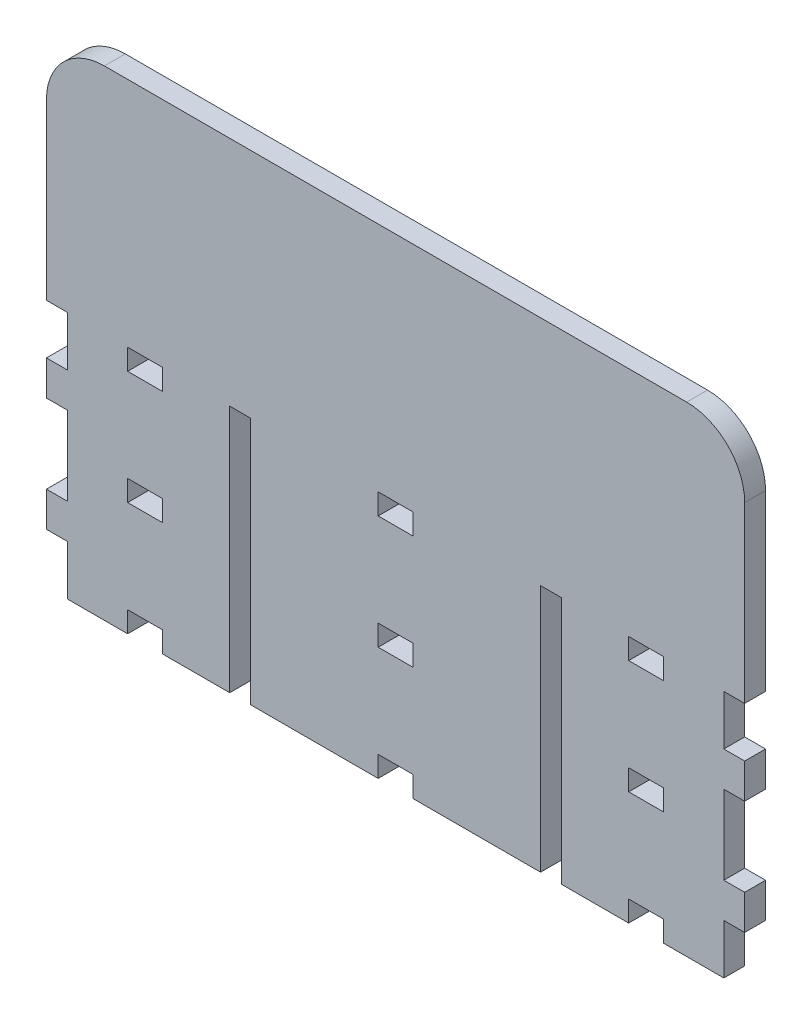
SolidWorks part; units mm, degrees
ref_plane "Plan de face" through (0, 0, 0) normal (0, 0, 1) x (1, 0, 0)
ref_plane "Plan de dessus" through (0, 0, 0) normal (0, 1, 0) x (1, 0, 0)
ref_plane "Plan de droite" through (0, 0, 0) normal (1, 0, 0) x (0, 0, -1)
sketch "Esquisse1" plane through (0, 0, 0) normal (0, 0, 1) x (1, 0, 0)
  line L1 (-584, 400) -> (18, 400)
  line L2 (-584, 400) -> (-584, 764)
  line L3 (-534, 814) -> (-32, 814)
  line L4 (18, 400) -> (18, 764)
  line L8 (18, 614) -> (18, 571) construction
  line L9 (-584, 614) -> (-584, 571) construction
  line L10 (-566, 614) -> (-584, 614) construction
  arc A0 (-584, 764) -> (-534, 814) centre (-534, 764) cw
  arc A1 (-32, 814) -> (18, 764) centre (-32, 764) cw
  dimension "D2" = 50
  dimension "D1" = 200
extrude "Boss.-Extru.1" add sketch "Esquisse1" against normal blind 18
sketch "Esquisse2" plane through (0, 0, 0) normal (0, 0, 1) x (1, 0, 0)
  line L0 (-584, 400) -> (18, 400) construction
  line L1 (-514, 614) -> (-484, 614)
  line L2 (-514, 614) -> (-514, 596)
  line L3 (-514, 596) -> (-484, 596)
  line L4 (-484, 614) -> (-484, 596)
  line L5 (-298, 614) -> (-268, 614)
  line L6 (-298, 614) -> (-298, 596)
  line L7 (-298, 596) -> (-268, 596)
  line L8 (-268, 614) -> (-268, 596)
  line L9 (-82, 614) -> (-52, 614)
  line L10 (-82, 614) -> (-82, 596)
  line L11 (-82, 596) -> (-52, 596)
  line L12 (-52, 614) -> (-52, 596)
  line L13 (-82, 516) -> (-52, 516)
  line L14 (-82, 516) -> (-82, 498)
  line L15 (-82, 498) -> (-52, 498)
  line L16 (-52, 516) -> (-52, 498)
  line L17 (-298, 516) -> (-268, 516)
  line L18 (-298, 516) -> (-298, 498)
  line L19 (-298, 498) -> (-268, 498)
  line L20 (-268, 516) -> (-268, 498)
  line L21 (-514, 516) -> (-484, 516)
  line L22 (-514, 516) -> (-514, 498)
  line L23 (-514, 498) -> (-484, 498)
  line L24 (-484, 516) -> (-484, 498)
  line L25 (-514, 418) -> (-484, 418)
  line L26 (-514, 418) -> (-514, 400)
  line L27 (-514, 400) -> (-484, 400)
  line L28 (-484, 418) -> (-484, 400)
  line L29 (-484, 400) -> (-484, 418) construction
  line L30 (-268, 400) -> (-268, 418) construction
  line L31 (-298, 418) -> (-268, 418)
  line L32 (-298, 418) -> (-298, 400)
  line L33 (-298, 400) -> (-268, 400)
  line L34 (-268, 418) -> (-268, 400)
  line L35 (-514, 605) -> (-584, 605) construction
  line L36 (-82, 418) -> (-52, 418)
  line L37 (-82, 418) -> (-82, 400)
  line L38 (-82, 400) -> (-52, 400)
  line L39 (-52, 418) -> (-52, 400)
  line L40 (-584, 764) -> (-584, 400) construction
  line L41 (-484, 605) -> (-298, 605) construction
  line L42 (-268, 605) -> (-82, 605) construction
  line L43 (-52, 605) -> (18, 605) construction
  line L44 (18, 400) -> (18, 764) construction
extrude "Enlèv. mat.-Extru.1" cut sketch "Esquisse2" against normal through all
sketch "Esquisse3" plane through (0, 0, 0) normal (0, 0, 1) x (1, 0, 0)
  line L0 (0, 614) -> (0, 10) construction
  line L1 (0, 443) -> (18, 443)
  line L2 (0, 443) -> (0, 400)
  line L3 (0, 400) -> (18, 400)
  line L4 (18, 443) -> (18, 400)
  line L5 (18, 400) -> (18, 764) construction
  line L6 (0, 473) -> (18, 473)
  line L7 (0, 473) -> (0, 541)
  line L8 (0, 541) -> (18, 541)
  line L9 (18, 473) -> (18, 541)
  line L10 (0, 541) -> (18, 541) construction
  line L11 (-584, 764) -> (-584, 400) construction
  line L12 (0, 571) -> (18, 571)
  line L13 (0, 571) -> (0, 614)
  line L14 (0, 614) -> (18, 614)
  line L15 (18, 571) -> (18, 614)
  line L16 (-566, 443) -> (-584, 443)
  line L17 (-566, 443) -> (-566, 400)
  line L18 (-566, 400) -> (-584, 400)
  line L19 (-584, 443) -> (-584, 400)
  line L20 (-584, 541) -> (-566, 541) construction
  line L21 (-566, 473) -> (-584, 473)
  line L22 (-566, 473) -> (-566, 541)
  line L23 (-566, 541) -> (-584, 541)
  line L24 (-584, 473) -> (-584, 541)
  line L25 (-566, 571) -> (-584, 571)
  line L26 (-566, 571) -> (-566, 614)
  line L27 (-566, 614) -> (-584, 614)
  line L28 (-584, 571) -> (-584, 614)
  line L29 (-584, 400) -> (-514, 400) construction
  line L30 (18, 614) -> (-584, 614) construction
  line L31 (18, 614) -> (0, 614) construction
  line L32 (0, 443) -> (18, 443) construction
extrude "Enlèv. mat.-Extru.2" cut sketch "Esquisse3" against normal through all
sketch "Esquisse4" plane through (0, 0, 0) normal (0, 0, 1) x (1, 0, 0)
  line L0 (-484, 400) -> (-298, 400) construction
  line L1 (-408, 400) -> (-426, 400)
  line L2 (-408, 400) -> (-408, 614)
  line L3 (-408, 614) -> (-426, 614)
  line L4 (-426, 400) -> (-426, 614)
  line L5 (-408, 614) -> (-408, 253.4124) construction
  line L6 (-268, 400) -> (-82, 400) construction
  line L7 (-158, 400) -> (-140, 400)
  line L8 (-158, 400) -> (-158, 614)
  line L9 (-158, 614) -> (-140, 614)
  line L10 (-140, 400) -> (-140, 614)
  line L11 (-158, 614) -> (-158, 253.4124) construction
extrude "Enlèv. mat.-Extru.3" cut sketch "Esquisse4" against normal blind 18
sketch "Esquisse6" plane through (0, 0, -18) normal (0, 0, 1) x (1, 0, 0)
  line L0 (-490.5423, 716.0008) -> (-490.5423, 701.5979)
  line L1 (-488.7785, 699.5812) -> (-488.7785, 717.8116)
  line L2 (-479.2535, 724.3917) -> (-479.2535, 693.0885)
  line L3 (-477.0486, 691.0866) -> (-477.0486, 726.1757)
  line L4 (-390.7062, 725.3692) -> (-390.7062, 690.4251)
  line L5 (-388.5014, 692.4312) -> (-388.5014, 723.353)
  line L6 (-379.0646, 716.7748) -> (-379.0646, 698.7223)
  line L7 (-377.3007, 700.9795) -> (-377.3007, 715.0627)
  line L8 (-477.0486, 726.1757) -> (-477.0486, 691.0866)
  line L9 (-390.7062, 690.4251) -> (-390.7062, 725.3692)
  line L10 (-488.7785, 717.8116) -> (-488.7785, 699.5812)
  line L11 (-479.2535, 693.0885) -> (-479.2535, 724.3917)
  line L12 (-388.5014, 723.353) -> (-388.5014, 692.4312)
  line L13 (-379.0646, 698.7223) -> (-379.0646, 716.7748)
  line L14 (-490.5423, 701.5979) -> (-490.5423, 716.0008)
  line L15 (-377.3007, 715.0627) -> (-377.3007, 700.9795)
  line L16 (-584, 714) -> (-433.5, 714) construction
  line L19 (-584, 764) -> (-584, 614) construction
  line L20 (-433.5, 714) -> (-283, 714) construction
  line L21 (-132.5, 714) -> (18, 714) construction
  line L22 (18, 614) -> (18, 764) construction
  line L23 (-283, 714) -> (-283, 814) construction
  line L24 (-32, 814) -> (-534, 814) construction
  line L25 (-283, 714) -> (-132.5, 714) construction
  line L26 (-508.2295, 707.4612) -> (-358.7705, 720.5388) construction
  line L27 (-283, 714) -> (-283, 614) construction
  line L28 (-268, 614) -> (-298, 614) construction
  line L29 (-207.242, 707.8567) -> (-57.758, 720.1433) construction
  spline S0 degree 3 poles (-167.9941, 780.5511) (-159.6923, 785.0594) (-149.9682, 788.1975) (-138.6433, 789.0831) knots 8 8 8 8 9 9 9 9
  spline S1 degree 3 poles (-188.8125, 763.828) (-183.1553, 770.3743) (-176.5566, 775.901) (-167.9941, 780.5511) knots 7 7 7 7 8 8 8 8
  spline S2 degree 3 poles (-207.242, 707.8567) (-209.3608, 732.9454) (-200.0954, 750.7719) (-188.8125, 763.828) knots 6 6 6 6 7 7 7 7
  spline S3 degree 3 poles (-182.3283, 658.0286) (-195.8761, 669.7994) (-205.3943, 685.9735) (-207.242, 707.8567) knots 5 5 5 5 6 6 6 6
  spline S4 degree 3 poles (-126.3571, 639.599) (-150.3082, 637.6326) (-169.3815, 646.78) (-182.3283, 658.0286) knots 4 4 4 4 5 5 5 5
  spline S5 degree 3 poles (-76.5286, 664.5129) (-88.3918, 650.9871) (-103.9374, 641.4394) (-126.3571, 639.599) knots 3 3 3 3 4 4 4 4
  spline S6 degree 3 poles (-57.758, 720.1433) (-55.8242, 695.4161) (-64.8483, 677.8317) (-76.5286, 664.5129) knots 2 2 2 2 3 3 3 3
  spline S7 degree 3 poles (-82.3311, 770.3125) (-69.5426, 759.036) (-59.5119, 742.5654) (-57.758, 720.1433) knots 1 1 1 1 2 2 2 2
  spline S8 degree 3 poles (-138.6433, 789.0831) (-114.19, 790.9955) (-95.1366, 781.6038) (-82.3311, 770.3125) knots 0 0 0 0 1 1 1 1
  spline S9 degree 3 poles (-174.1371, 731.4055) (-172.0509, 731.6973) (-172.8434, 734.2081) (-172.7721, 735.1596) knots 16 16 16 16 17 17 17 17
  spline S10 degree 3 poles (-176.185, 739.5964) (-176.082, 736.8451) (-176.745, 732.0371) (-174.1371, 731.4055) knots 15 15 15 15 16 16 16 16
  spline S11 degree 3 poles (-175.844, 751.5414) (-176.5898, 748.4845) (-176.3518, 744.0505) (-176.185, 739.5964) knots 14 14 14 14 15 15 15 15
  spline S12 degree 3 poles (-137.6194, 777.8207) (-154.7803, 776.5585) (-172.0452, 767.1012) (-175.844, 751.5414) knots 13 13 13 13 14 14 14 14
  spline S13 degree 3 poles (-114.4115, 773.7252) (-122.2829, 776.2977) (-128.8265, 778.4676) (-137.6194, 777.8207) knots 12 12 12 12 13 13 13 13
  spline S14 degree 3 poles (-99.7368, 767.5821) (-103.0613, 770.1785) (-108.7891, 771.8874) (-114.4115, 773.7252) knots 11 11 11 11 12 12 12 12
  spline S15 degree 3 poles (-90.8633, 753.5891) (-91.6605, 758.6655) (-96.7933, 765.2835) (-99.7368, 767.5821) knots 10 10 10 10 11 11 11 11
  spline S16 degree 3 poles (-91.8871, 737.549) (-91.0445, 741.3206) (-90.4619, 751.0313) (-90.8633, 753.5891) knots 9 9 9 9 10 10 10 10
  spline S17 degree 3 poles (-94.617, 742.3266) (-94.8434, 740.0665) (-96.3113, 734.5149) (-93.9342, 734.1357) (-92.149, 733.851) (-92.4642, 734.9644) (-91.8871, 737.549) knots 7 7 7 7 8 8 8 9 9 9 9
  spline S18 degree 3 poles (-93.9342, 751.5414) (-93.7065, 748.9638) (-94.2732, 745.7652) (-94.617, 742.3266) knots 6 6 6 6 7 7 7 7
  spline S19 degree 3 poles (-102.4667, 765.5343) (-99.033, 763.1209) (-94.3821, 756.5986) (-93.9342, 751.5414) knots 5 5 5 5 6 6 6 6
  spline S20 degree 3 poles (-115.7775, 770.6534) (-110.8796, 769.0702) (-105.5762, 767.7199) (-102.4667, 765.5343) knots 4 4 4 4 5 5 5 5
  spline S21 degree 3 poles (-137.9608, 774.4077) (-128.5364, 775.0831) (-122.862, 772.9442) (-115.7775, 770.6534) knots 3 3 3 3 4 4 4 4
  spline S22 degree 3 poles (-164.2398, 764.5104) (-157.7886, 769.8863) (-147.0569, 773.7562) (-137.9608, 774.4077) knots 2 2 2 2 3 3 3 3
  spline S23 degree 3 poles (-172.7721, 750.8589) (-172.0609, 755.3882) (-168.2716, 761.1506) (-164.2398, 764.5104) knots 1 1 1 1 2 2 2 2
  spline S24 degree 3 poles (-172.7721, 735.1596) (-172.368, 740.5501) (-173.5516, 745.8935) (-172.7721, 750.8589) knots 0 0 0 0 1 1 1 1
  spline S25 degree 3 poles (-99.3957, 739.9378) (-99.5122, 743.1073) (-103.8254, 743.9258) (-106.5622, 744.7158) knots 14 14 14 14 15 15 15 15
  spline S26 degree 3 poles (-106.9033, 741.3027) (-104.4883, 740.5787) (-101.7828, 738.4056) (-99.3957, 739.9378) knots 13 13 13 13 14 14 14 14
  spline S27 degree 3 poles (-124.3089, 743.0094) (-117.1817, 743.2909) (-111.7712, 742.7617) (-106.9033, 741.3027) knots 12 12 12 12 13 13 13 13
  spline S28 degree 3 poles (-123.6268, 739.9378) (-122.2005, 741.2573) (-124.6431, 742.8385) (-124.3089, 743.0094) knots 11 11 11 11 12 12 12 12
  spline S29 degree 3 poles (-128.7459, 741.3027) (-127.1353, 740.9332) (-125.4755, 738.584) (-123.6268, 739.9378) knots 10 10 10 10 11 11 11 11
  spline S30 degree 3 poles (-142.3974, 740.6203) (-137.8723, 740.3119) (-133.0764, 742.2959) (-128.7459, 741.3027) knots 9 9 9 9 10 10 10 10
  spline S31 degree 3 poles (-159.8032, 748.4701) (-154.3956, 745.5312) (-150.2421, 741.1549) (-142.3974, 740.6203) knots 8 8 8 8 9 9 9 9
  spline S32 degree 3 poles (-162.8749, 738.2314) (-161.3782, 741.028) (-159.9352, 744.6185) (-159.8032, 748.4701) knots 7 7 7 7 8 8 8 8
  spline S33 degree 3 poles (-166.6292, 735.501) (-164.1361, 734.1002) (-163.7436, 736.6078) (-162.8749, 738.2314) knots 6 6 6 6 7 7 7 7
  spline S34 degree 3 poles (-163.216, 749.835) (-162.1876, 744.4312) (-166.8082, 739.6362) (-166.6292, 735.501) knots 5 5 5 5 6 6 6 6
  spline S35 degree 3 poles (-165.6051, 754.6132) (-165.278, 752.2642) (-163.6009, 751.8575) (-163.216, 749.835) knots 4 4 4 4 5 5 5 5
  spline S36 degree 3 poles (-159.4617, 752.5653) (-161.8629, 754.4635) (-164.0798, 757.2676) (-165.6051, 754.6132) knots 3 3 3 3 4 4 4 4
  spline S37 degree 3 poles (-133.5241, 744.7158) (-145.626, 742.4834) (-152.6762, 747.2009) (-159.4617, 752.5653) knots 2 2 2 2 3 3 3 3
  spline S38 degree 3 poles (-130.7938, 745.7398) (-131.7319, 745.5304) (-132.5014, 744.9042) (-133.5241, 744.7158) knots 1 1 1 1 2 2 2 2
  spline S39 degree 3 poles (-106.5622, 744.7158) (-113.3842, 746.6841) (-122.9151, 747.498) (-130.7938, 745.7398) knots 0 0 0 0 1 1 1 1
  spline S40 degree 3 poles (-165.2637, 731.7469) (-167.5814, 731.2949) (-169.2893, 730.8786) (-170.0419, 729.0165) knots 14 14 14 14 15 15 15 15
  spline S41 degree 3 poles (-164.9223, 732.0883) (-165.1943, 732.0681) (-165.2227, 731.7546) (-165.2637, 731.7469) knots 13 13 13 13 14 14 14 14
  spline S42 degree 3 poles (-95.6409, 729.3575) (-97.5478, 732.6578) (-105.3303, 732.0883) (-110.6578, 732.0883) (-116.7521, 732.0883) (-123.3829, 732.0883) (-128.7459, 732.0883) (-142.7666, 732.0883) (-152.9966, 732.9637) (-164.9223, 732.0883) knots 10 10 10 10 11 11 11 12 12 12 13 13 13 13
  spline S43 degree 3 poles (-97.3476, 713.3172) (-96.4016, 716.3916) (-93.6156, 725.8527) (-95.6409, 729.3575) knots 9 9 9 9 10 10 10 10
  spline S44 degree 3 poles (-105.1973, 702.3962) (-100.7211, 703.8094) (-98.7419, 708.7865) (-97.3476, 713.3172) knots 8 8 8 8 9 9 9 9
  spline S45 degree 3 poles (-121.238, 702.3962) (-117.7043, 701.239) (-108.4047, 701.3834) (-105.1973, 702.3962) knots 7 7 7 7 8 8 8 8
  spline S46 degree 3 poles (-126.6981, 707.5153) (-125.4748, 705.7028) (-123.0477, 702.9888) (-121.238, 702.3962) knots 6 6 6 6 7 7 7 7
  spline S47 degree 3 poles (-131.8177, 712.9758) (-128.7211, 712.8976) (-128.1437, 709.6564) (-126.6981, 707.5153) knots 5 5 5 5 6 6 6 6
  spline S48 degree 3 poles (-136.9369, 707.5153) (-135.7604, 709.2409) (-135.4226, 713.0678) (-131.8177, 712.9758) knots 4 4 4 4 5 5 5 5
  spline S49 degree 3 poles (-142.3974, 702.3962) (-140.443, 703.089) (-138.1239, 705.7748) (-136.9369, 707.5153) knots 3 3 3 3 4 4 4 4
  spline S50 degree 3 poles (-159.8032, 702.7373) (-156.4706, 701.4729) (-145.5979, 701.2618) (-142.3974, 702.3962) knots 2 2 2 2 3 3 3 3
  spline S51 degree 3 poles (-167.6525, 713.6589) (-166.2037, 709.4842) (-164.2503, 704.4247) (-159.8032, 702.7373) knots 1 1 1 1 2 2 2 2
  spline S52 degree 3 poles (-170.0419, 729.0165) (-171.618, 725.1175) (-168.3257, 715.5975) (-167.6525, 713.6589) knots 0 0 0 0 1 1 1 1
  spline S53 degree 3 poles (-96.3237, 691.1335) (-89.767, 695.1174) (-83.3282, 708.8751) (-84.72, 720.1433) knots 21 21 21 21 22 22 22 22
  spline S54 degree 3 poles (-111.3399, 657.6875) (-102.9487, 666.2265) (-98.6178, 677.6556) (-96.3237, 691.1335) knots 20 20 20 20 21 21 21 21
  spline S55 degree 3 poles (-120.5552, 650.8617) (-117.3895, 651.5494) (-113.9385, 655.0437) (-111.3399, 657.6875) knots 19 19 19 19 20 20 20 20
  spline S56 degree 3 poles (-140.6911, 650.8617) (-137.8675, 650.3863) (-134.3204, 650.8617) (-130.7938, 650.8617) (-127.5869, 650.8617) (-123.6237, 650.1951) (-120.5552, 650.8617) knots 17 17 17 17 18 18 18 19 19 19 19
  spline S57 degree 3 poles (-153.3187, 658.37) (-150.3051, 655.3879) (-145.1576, 651.6135) (-140.6911, 650.8617) knots 16 16 16 16 17 17 17 17
  spline S58 degree 3 poles (-168.3355, 691.4749) (-166.0678, 679.4946) (-161.2085, 666.1759) (-153.3187, 658.37) knots 15 15 15 15 16 16 16 16
  spline S59 degree 3 poles (-180.2805, 714.3411) (-179.5331, 704.6383) (-174.8947, 693.9743) (-168.3355, 691.4749) knots 14 14 14 14 15 15 15 15
  spline S60 degree 3 poles (-176.5264, 725.9448) (-181.1213, 725.5385) (-180.6059, 718.5644) (-180.2805, 714.3411) knots 13 13 13 13 14 14 14 14
  spline S61 degree 3 poles (-177.2089, 719.1194) (-177.0249, 721.82) (-174.6394, 724.1127) (-176.5264, 725.9448) knots 12 12 12 12 13 13 13 13
  spline S62 degree 3 poles (-169.3594, 695.5701) (-173.8599, 698.1333) (-177.6533, 712.5916) (-177.2089, 719.1194) knots 11 11 11 11 12 12 12 12
  spline S63 degree 3 poles (-165.2637, 694.8876) (-166.635, 694.7702) (-168.2553, 694.9414) (-169.3594, 695.5701) knots 10 10 10 10 11 11 11 11
  spline S64 degree 3 poles (-150.5883, 660.4177) (-159.1023, 668.4669) (-163.5458, 681.8907) (-165.2637, 694.8876) knots 9 9 9 9 10 10 10 10
  spline S65 degree 3 poles (-140.3497, 654.2744) (-143.9005, 654.8704) (-147.8212, 657.8015) (-150.5883, 660.4177) knots 8 8 8 8 9 9 9 9
  spline S66 degree 3 poles (-121.238, 654.2744) (-124.0792, 653.6357) (-127.959, 654.2744) (-130.7938, 654.2744) (-134.2536, 654.2744) (-137.6015, 653.8131) (-140.3497, 654.2744) knots 6 6 6 6 7 7 7 8 8 8 8
  spline S67 degree 3 poles (-112.3638, 661.1002) (-114.8304, 658.4564) (-118.4027, 654.9118) (-121.238, 654.2744) knots 5 5 5 5 6 6 6 6
  spline S68 degree 3 poles (-99.3957, 694.5462) (-101.1286, 681.12) (-104.8166, 669.1917) (-112.3638, 661.1002) knots 4 4 4 4 5 5 5 5
  spline S69 degree 3 poles (-96.3237, 694.8876) (-97.4327, 694.1046) (-98.4359, 695.3372) (-99.3957, 694.5462) knots 3 3 3 3 4 4 4 4
  spline S70 degree 3 poles (-88.1327, 720.4844) (-86.158, 711.0861) (-92.1162, 700.1445) (-96.3237, 694.8876) knots 2 2 2 2 3 3 3 3
  spline S71 degree 3 poles (-90.5215, 726.2862) (-90.2931, 724.2981) (-88.626, 722.831) (-88.1327, 720.4844) knots 1 1 1 1 2 2 2 2
  spline S72 degree 3 poles (-84.72, 720.1433) (-85.1317, 723.4754) (-88.3521, 730.7017) (-90.5215, 726.2862) knots 0 0 0 0 1 1 1 1
  spline S73 degree 3 poles (-172.7721, 735.1596) (-172.8434, 734.2081) (-172.0509, 731.6973) (-174.1371, 731.4055) knots 16 16 16 16 17 17 17 17
  spline S74 degree 3 poles (-172.7721, 750.8589) (-173.5516, 745.8935) (-172.368, 740.5501) (-172.7721, 735.1596) knots 15 15 15 15 16 16 16 16
  spline S75 degree 3 poles (-164.2398, 764.5104) (-168.2716, 761.1506) (-172.0609, 755.3882) (-172.7721, 750.8589) knots 14 14 14 14 15 15 15 15
  spline S76 degree 3 poles (-137.9608, 774.4077) (-147.0569, 773.7562) (-157.7886, 769.8863) (-164.2398, 764.5104) knots 13 13 13 13 14 14 14 14
  spline S77 degree 3 poles (-115.7775, 770.6534) (-122.862, 772.9442) (-128.5364, 775.0831) (-137.9608, 774.4077) knots 12 12 12 12 13 13 13 13
  spline S78 degree 3 poles (-102.4667, 765.5343) (-105.5762, 767.7199) (-110.8796, 769.0702) (-115.7775, 770.6534) knots 11 11 11 11 12 12 12 12
  spline S79 degree 3 poles (-93.9342, 751.5414) (-94.3821, 756.5986) (-99.033, 763.1209) (-102.4667, 765.5343) knots 10 10 10 10 11 11 11 11
  spline S80 degree 3 poles (-94.617, 742.3266) (-94.2732, 745.7652) (-93.7065, 748.9638) (-93.9342, 751.5414) knots 9 9 9 9 10 10 10 10
  spline S81 degree 3 poles (-91.8871, 737.549) (-92.4642, 734.9644) (-92.149, 733.851) (-93.9342, 734.1357) (-96.3113, 734.5149) (-94.8434, 740.0665) (-94.617, 742.3266) knots 7 7 7 7 8 8 8 9 9 9 9
  spline S82 degree 3 poles (-90.8633, 753.5891) (-90.4619, 751.0313) (-91.0445, 741.3206) (-91.8871, 737.549) knots 6 6 6 6 7 7 7 7
  spline S83 degree 3 poles (-99.7368, 767.5821) (-96.7933, 765.2835) (-91.6605, 758.6655) (-90.8633, 753.5891) knots 5 5 5 5 6 6 6 6
  spline S84 degree 3 poles (-114.4115, 773.7252) (-108.7891, 771.8874) (-103.0613, 770.1785) (-99.7368, 767.5821) knots 4 4 4 4 5 5 5 5
  spline S85 degree 3 poles (-137.6194, 777.8207) (-128.8265, 778.4676) (-122.2829, 776.2977) (-114.4115, 773.7252) knots 3 3 3 3 4 4 4 4
  spline S86 degree 3 poles (-175.844, 751.5414) (-172.0452, 767.1012) (-154.7803, 776.5585) (-137.6194, 777.8207) knots 2 2 2 2 3 3 3 3
  spline S87 degree 3 poles (-176.185, 739.5964) (-176.3518, 744.0505) (-176.5898, 748.4845) (-175.844, 751.5414) knots 1 1 1 1 2 2 2 2
  spline S88 degree 3 poles (-174.1371, 731.4055) (-176.745, 732.0371) (-176.082, 736.8451) (-176.185, 739.5964) knots 0 0 0 0 1 1 1 1
  spline S89 degree 3 poles (-106.5622, 744.7158) (-103.8254, 743.9258) (-99.5122, 743.1073) (-99.3957, 739.9378) knots 14 14 14 14 15 15 15 15
  spline S90 degree 3 poles (-130.7938, 745.7398) (-122.9151, 747.498) (-113.3842, 746.6841) (-106.5622, 744.7158) knots 13 13 13 13 14 14 14 14
  spline S91 degree 3 poles (-133.5241, 744.7158) (-132.5014, 744.9042) (-131.7319, 745.5304) (-130.7938, 745.7398) knots 12 12 12 12 13 13 13 13
  spline S92 degree 3 poles (-159.4617, 752.5653) (-152.6762, 747.2009) (-145.626, 742.4834) (-133.5241, 744.7158) knots 11 11 11 11 12 12 12 12
  spline S93 degree 3 poles (-165.6051, 754.6132) (-164.0798, 757.2676) (-161.8629, 754.4635) (-159.4617, 752.5653) knots 10 10 10 10 11 11 11 11
  spline S94 degree 3 poles (-163.216, 749.835) (-163.6009, 751.8575) (-165.278, 752.2642) (-165.6051, 754.6132) knots 9 9 9 9 10 10 10 10
  spline S95 degree 3 poles (-166.6292, 735.501) (-166.8082, 739.6362) (-162.1876, 744.4312) (-163.216, 749.835) knots 8 8 8 8 9 9 9 9
  spline S96 degree 3 poles (-162.8749, 738.2314) (-163.7436, 736.6078) (-164.1361, 734.1002) (-166.6292, 735.501) knots 7 7 7 7 8 8 8 8
  spline S97 degree 3 poles (-159.8032, 748.4701) (-159.9352, 744.6185) (-161.3782, 741.028) (-162.8749, 738.2314) knots 6 6 6 6 7 7 7 7
  spline S98 degree 3 poles (-142.3974, 740.6203) (-150.2421, 741.1549) (-154.3956, 745.5312) (-159.8032, 748.4701) knots 5 5 5 5 6 6 6 6
  spline S99 degree 3 poles (-128.7459, 741.3027) (-133.0764, 742.2959) (-137.8723, 740.3119) (-142.3974, 740.6203) knots 4 4 4 4 5 5 5 5
  spline S100 degree 3 poles (-123.6268, 739.9378) (-125.4755, 738.584) (-127.1353, 740.9332) (-128.7459, 741.3027) knots 3 3 3 3 4 4 4 4
  spline S101 degree 3 poles (-124.3089, 743.0094) (-124.6431, 742.8385) (-122.2005, 741.2573) (-123.6268, 739.9378) knots 2 2 2 2 3 3 3 3
  spline S102 degree 3 poles (-106.9033, 741.3027) (-111.7712, 742.7617) (-117.1817, 743.2909) (-124.3089, 743.0094) knots 1 1 1 1 2 2 2 2
  spline S103 degree 3 poles (-99.3957, 739.9378) (-101.7828, 738.4056) (-104.4883, 740.5787) (-106.9033, 741.3027) knots 0 0 0 0 1 1 1 1
  spline S104 degree 3 poles (-170.0419, 729.0165) (-169.2893, 730.8786) (-167.5814, 731.2949) (-165.2637, 731.7469) knots 14 14 14 14 15 15 15 15
  spline S105 degree 3 poles (-167.6525, 713.6589) (-168.3257, 715.5975) (-171.618, 725.1175) (-170.0419, 729.0165) knots 13 13 13 13 14 14 14 14
  spline S106 degree 3 poles (-159.8032, 702.7373) (-164.2503, 704.4247) (-166.2037, 709.4842) (-167.6525, 713.6589) knots 12 12 12 12 13 13 13 13
  spline S107 degree 3 poles (-142.3974, 702.3962) (-145.5979, 701.2618) (-156.4706, 701.4729) (-159.8032, 702.7373) knots 11 11 11 11 12 12 12 12
  spline S108 degree 3 poles (-136.9369, 707.5153) (-138.1239, 705.7748) (-140.443, 703.089) (-142.3974, 702.3962) knots 10 10 10 10 11 11 11 11
  spline S109 degree 3 poles (-131.8177, 712.9758) (-135.4226, 713.0678) (-135.7604, 709.2409) (-136.9369, 707.5153) knots 9 9 9 9 10 10 10 10
  spline S110 degree 3 poles (-126.6981, 707.5153) (-128.1437, 709.6564) (-128.7211, 712.8976) (-131.8177, 712.9758) knots 8 8 8 8 9 9 9 9
  spline S111 degree 3 poles (-121.238, 702.3962) (-123.0477, 702.9888) (-125.4748, 705.7028) (-126.6981, 707.5153) knots 7 7 7 7 8 8 8 8
  spline S112 degree 3 poles (-105.1973, 702.3962) (-108.4047, 701.3834) (-117.7043, 701.239) (-121.238, 702.3962) knots 6 6 6 6 7 7 7 7
  spline S113 degree 3 poles (-97.3476, 713.3172) (-98.7419, 708.7865) (-100.7211, 703.8094) (-105.1973, 702.3962) knots 5 5 5 5 6 6 6 6
  spline S114 degree 3 poles (-95.6409, 729.3575) (-93.6156, 725.8527) (-96.4016, 716.3916) (-97.3476, 713.3172) knots 4 4 4 4 5 5 5 5
  spline S115 degree 3 poles (-164.9223, 732.0883) (-152.9966, 732.9637) (-142.7666, 732.0883) (-128.7459, 732.0883) (-123.3829, 732.0883) (-116.7521, 732.0883) (-110.6578, 732.0883) (-105.3303, 732.0883) (-97.5478, 732.6578) (-95.6409, 729.3575) knots 1 1 1 1 2 2 2 3 3 3 4 4 4 4
  spline S116 degree 3 poles (-165.2637, 731.7469) (-165.2227, 731.7546) (-165.1943, 732.0681) (-164.9223, 732.0883) knots 0 0 0 0 1 1 1 1
  spline S117 degree 3 poles (-84.72, 720.1433) (-83.3282, 708.8751) (-89.767, 695.1174) (-96.3237, 691.1335) knots 21 21 21 21 22 22 22 22
  spline S118 degree 3 poles (-90.5215, 726.2862) (-88.3521, 730.7017) (-85.1317, 723.4754) (-84.72, 720.1433) knots 20 20 20 20 21 21 21 21
  spline S119 degree 3 poles (-88.1327, 720.4844) (-88.626, 722.831) (-90.2931, 724.2981) (-90.5215, 726.2862) knots 19 19 19 19 20 20 20 20
  spline S120 degree 3 poles (-96.3237, 694.8876) (-92.1162, 700.1445) (-86.158, 711.0861) (-88.1327, 720.4844) knots 18 18 18 18 19 19 19 19
  spline S121 degree 3 poles (-99.3957, 694.5462) (-98.4359, 695.3372) (-97.4327, 694.1046) (-96.3237, 694.8876) knots 17 17 17 17 18 18 18 18
  spline S122 degree 3 poles (-112.3638, 661.1002) (-104.8166, 669.1917) (-101.1286, 681.12) (-99.3957, 694.5462) knots 16 16 16 16 17 17 17 17
  spline S123 degree 3 poles (-121.238, 654.2744) (-118.4027, 654.9118) (-114.8304, 658.4564) (-112.3638, 661.1002) knots 15 15 15 15 16 16 16 16
  spline S124 degree 3 poles (-140.3497, 654.2744) (-137.6015, 653.8131) (-134.2536, 654.2744) (-130.7938, 654.2744) (-127.959, 654.2744) (-124.0792, 653.6357) (-121.238, 654.2744) knots 13 13 13 13 14 14 14 15 15 15 15
  spline S125 degree 3 poles (-150.5883, 660.4177) (-147.8212, 657.8015) (-143.9005, 654.8704) (-140.3497, 654.2744) knots 12 12 12 12 13 13 13 13
  spline S126 degree 3 poles (-165.2637, 694.8876) (-163.5458, 681.8907) (-159.1023, 668.4669) (-150.5883, 660.4177) knots 11 11 11 11 12 12 12 12
  spline S127 degree 3 poles (-169.3594, 695.5701) (-168.2553, 694.9414) (-166.635, 694.7702) (-165.2637, 694.8876) knots 10 10 10 10 11 11 11 11
  spline S128 degree 3 poles (-177.2089, 719.1194) (-177.6533, 712.5916) (-173.8599, 698.1333) (-169.3594, 695.5701) knots 9 9 9 9 10 10 10 10
  spline S129 degree 3 poles (-176.5264, 725.9448) (-174.6394, 724.1127) (-177.0249, 721.82) (-177.2089, 719.1194) knots 8 8 8 8 9 9 9 9
  spline S130 degree 3 poles (-180.2805, 714.3411) (-180.6059, 718.5644) (-181.1213, 725.5385) (-176.5264, 725.9448) knots 7 7 7 7 8 8 8 8
  spline S131 degree 3 poles (-168.3355, 691.4749) (-174.8947, 693.9743) (-179.5331, 704.6383) (-180.2805, 714.3411) knots 6 6 6 6 7 7 7 7
  spline S132 degree 3 poles (-153.3187, 658.37) (-161.2085, 666.1759) (-166.0678, 679.4946) (-168.3355, 691.4749) knots 5 5 5 5 6 6 6 6
  spline S133 degree 3 poles (-140.6911, 650.8617) (-145.1576, 651.6135) (-150.3051, 655.3879) (-153.3187, 658.37) knots 4 4 4 4 5 5 5 5
  spline S134 degree 3 poles (-120.5552, 650.8617) (-123.6237, 650.1951) (-127.5869, 650.8617) (-130.7938, 650.8617) (-134.3204, 650.8617) (-137.8675, 650.3863) (-140.6911, 650.8617) knots 2 2 2 2 3 3 3 4 4 4 4
  spline S135 degree 3 poles (-111.3399, 657.6875) (-113.9385, 655.0437) (-117.3895, 651.5494) (-120.5552, 650.8617) knots 1 1 1 1 2 2 2 2
  spline S136 degree 3 poles (-96.3237, 691.1335) (-98.6178, 677.6556) (-102.9487, 666.2265) (-111.3399, 657.6875) knots 0 0 0 0 1 1 1 1
  spline S137 degree 3 poles (-377.1419, 664.4916) (-365.5825, 677.6887) (-356.8151, 696.6061) (-358.7705, 720.5388) knots 8 8 8 8 9 9 9 9
  spline S138 degree 3 poles (-426.961, 639.5818) (-404.9193, 641.3915) (-388.8032, 651.177) (-377.1419, 664.4916) knots 7 7 7 7 8 8 8 8
  spline S139 degree 3 poles (-483.0083, 657.9531) (-470.0559, 646.5778) (-451.2724, 637.5861) (-426.961, 639.5818) knots 6 6 6 6 7 7 7 7
  spline S140 degree 3 poles (-508.2295, 707.4612) (-506.3247, 685.4188) (-496.4657, 669.7715) (-483.0083, 657.9531) knots 5 5 5 5 6 6 6 6
  spline S141 degree 3 poles (-490.1699, 763.8197) (-501.4499, 750.9404) (-510.3565, 732.074) (-508.2295, 707.4612) knots 4 4 4 4 5 5 5 5
  spline S142 degree 3 poles (-469.308, 780.3224) (-477.6909, 775.6553) (-484.5331, 770.255) (-490.1699, 763.8197) knots 3 3 3 3 4 4 4 4
  spline S143 degree 3 poles (-440.0386, 789.0406) (-451.1821, 788.1693) (-461.1662, 784.8549) (-469.308, 780.3224) knots 2 2 2 2 3 3 3 3
  spline S144 degree 3 poles (-383.6803, 770.3585) (-396.6993, 781.7457) (-415.0203, 790.997) (-440.0386, 789.0406) knots 1 1 1 1 2 2 2 2
  spline S145 degree 3 poles (-358.7705, 720.5388) (-360.615, 743.1123) (-370.6279, 758.942) (-383.6803, 770.3585) knots 0 0 0 0 1 1 1 1
  spline S146 degree 3 poles (-490.7926, 715.997) (-490.6972, 716.0103) (-490.615, 716.0103) (-490.5423, 716.0008) knots 0 0 0 0 1 1 1 1
  spline S147 degree 3 poles (-490.5423, 701.5979) (-494.0098, 704.0944) (-493.4982, 713.1893) (-490.7926, 715.997) knots 2 2 2 2 3 3 3 3
  spline S148 degree 3 poles (-488.7785, 717.8116) (-486.8926, 721.1878) (-483.5708, 723.1289) (-479.5831, 724.4038) knots 1 1 1 1 2 2 2 2
  spline S149 degree 3 poles (-479.5831, 724.4038) (-479.4793, 724.4038) (-479.3758, 724.4038) (-479.2719, 724.4038) knots 2 2 2 2 3 3 3 3
  spline S150 degree 3 poles (-479.2719, 724.4038) (-479.2652, 724.4001) (-479.26, 724.3955) (-479.2535, 724.3917) knots 3 3 3 3 4 4 4 4
  spline S151 degree 3 poles (-479.2535, 693.0885) (-483.5984, 694.083) (-486.6966, 696.3238) (-488.7785, 699.5812) knots 5 5 5 5 6 6 6 6
  spline S152 degree 3 poles (-469.308, 691.3984) (-471.2722, 690.8478) (-475.4819, 691.0649) (-477.0486, 691.0866) knots 0 0 0 0 1 1 1 1
  spline S153 degree 3 poles (-477.0486, 726.1757) (-475.3502, 727.0136) (-471.3881, 726.6341) (-469.6192, 726.272) knots 2 2 2 2 3 3 3 3
  spline S154 degree 3 poles (-469.6192, 726.272) (-468.8947, 715.2684) (-469.514, 702.9208) (-469.308, 691.3984) knots 3 3 3 3 4 4 4 4
  spline S155 degree 3 poles (-468.9965, 738.7273) (-469.3829, 735.5986) (-468.3129, 732.5707) (-468.9965, 728.7632) knots 14 14 14 14 15 15 15 15
  spline S156 degree 3 poles (-436.9249, 760.8348) (-451.7793, 759.968) (-467.3972, 751.6732) (-468.9965, 738.7273) knots 13 13 13 13 14 14 14 14
  spline S157 degree 3 poles (-419.7997, 757.7208) (-425.3625, 759.5193) (-430.0031, 761.2385) (-436.9249, 760.8348) knots 12 12 12 12 13 13 13 13
  spline S158 degree 3 poles (-407.9675, 753.3615) (-410.8683, 755.2377) (-415.3418, 756.2797) (-419.7997, 757.7208) knots 11 11 11 11 12 12 12 12
  spline S159 degree 3 poles (-399.8719, 741.5297) (-400.5072, 745.8181) (-404.3326, 751.0107) (-407.9675, 753.3615) knots 10 10 10 10 11 11 11 11
  spline S160 degree 3 poles (-400.8062, 726.272) (-401.1411, 731.3663) (-399.1026, 736.3367) (-399.8719, 741.5297) knots 9 9 9 9 10 10 10 10
  spline S161 degree 3 poles (-398.0036, 728.1403) (-399.237, 728.0142) (-400.3814, 726.1725) (-400.8062, 726.272) knots 8 8 8 8 9 9 9 9
  spline S162 degree 3 poles (-397.0697, 740.5955) (-396.8189, 736.7534) (-398.0908, 732.7192) (-398.0036, 728.1403) knots 7 7 7 7 8 8 8 8
  spline S163 degree 3 poles (-406.4104, 755.5414) (-402.1967, 752.8162) (-397.461, 746.5943) (-397.0697, 740.5955) knots 6 6 6 6 7 7 7 7
  spline S164 degree 3 poles (-419.7997, 760.5233) (-414.9507, 759.0203) (-409.7507, 757.7011) (-406.4104, 755.5414) knots 5 5 5 5 6 6 6 6
  spline S165 degree 3 poles (-471.4875, 739.3501) (-469.8687, 753.9305) (-451.1775, 763.3454) (-435.6799, 763.6369) (-430.34, 763.7373) (-424.2849, 761.9136) (-419.7997, 760.5233) knots 3 3 3 3 4 4 4 5 5 5 5
  spline S166 degree 3 poles (-470.8648, 728.7632) (-472.0098, 729.5776) (-471.4875, 731.8477) (-471.4875, 733.7453) (-471.4875, 735.7199) (-471.673, 737.6774) (-471.4875, 739.3501) knots 1 1 1 1 2 2 2 3 3 3 3
  spline S167 degree 3 poles (-468.9965, 728.7632) (-469.7939, 728.4256) (-470.4809, 729.7092) (-470.8648, 728.7632) knots 0 0 0 0 1 1 1 1
  spline S168 degree 3 poles (-426.3385, 733.434) (-427.1164, 732.805) (-424.3917, 731.8586) (-425.7156, 730.6316) knots 15 15 15 15 16 16 16 16
  spline S169 degree 3 poles (-411.7044, 732.1881) (-415.8547, 733.3245) (-420.5573, 733.4204) (-426.3385, 733.434) knots 14 14 14 14 15 15 15 15
  spline S170 degree 3 poles (-404.8539, 730.3197) (-407.3243, 729.4519) (-409.3704, 731.5494) (-411.7044, 732.1881) knots 13 13 13 13 14 14 14 14
  spline S171 degree 3 poles (-410.4583, 734.3684) (-408.4843, 733.776) (-404.8335, 733.2394) (-404.8539, 730.3197) knots 12 12 12 12 13 13 13 13
  spline S172 degree 3 poles (-427.8953, 735.9247) (-421.6484, 736.3796) (-415.5188, 735.8845) (-410.4583, 734.3684) knots 11 11 11 11 12 12 12 12
  spline S173 degree 3 poles (-440.9729, 733.7453) (-436.6356, 733.6745) (-432.1938, 735.6122) (-427.8953, 735.9247) knots 10 10 10 10 11 11 11 11
  spline S174 degree 3 poles (-461.2122, 744.3321) (-456.1475, 741.5269) (-449.3633, 733.8821) (-440.9729, 733.7453) knots 9 9 9 9 10 10 10 10
  spline S175 degree 3 poles (-462.1463, 743.7092) (-461.895, 743.9767) (-461.2935, 743.8944) (-461.2122, 744.3321) knots 8 8 8 8 9 9 9 9
  spline S176 degree 3 poles (-460.278, 739.3501) (-460.6432, 741.1981) (-462.1517, 741.3595) (-462.1463, 743.7092) knots 7 7 7 7 8 8 8 8
  spline S177 degree 3 poles (-462.1463, 730.9427) (-461.2049, 733.0964) (-459.5069, 735.4494) (-460.278, 739.3501) knots 6 6 6 6 7 7 7 7
  spline S178 degree 3 poles (-462.4578, 726.5838) (-464.3431, 727.4923) (-462.7325, 729.6014) (-462.1463, 730.9427) knots 5 5 5 5 6 6 6 6
  spline S179 degree 3 poles (-458.0985, 734.0564) (-458.8709, 730.9115) (-460.1159, 726.9052) (-462.4578, 726.5838) knots 4 4 4 4 5 5 5 5
  spline S180 degree 3 poles (-457.1644, 738.1042) (-457.8663, 736.9909) (-457.7442, 735.4992) (-458.0985, 734.0564) knots 3 3 3 3 4 4 4 4
  spline S181 degree 3 poles (-441.9072, 731.254) (-448.7607, 731.6951) (-452.4959, 735.4393) (-457.1644, 738.1042) knots 2 2 2 2 3 3 3 3
  spline S182 degree 3 poles (-430.6979, 731.877) (-434.4396, 732.5518) (-438.3677, 731.0266) (-441.9072, 731.254) knots 1 1 1 1 2 2 2 2
  spline S183 degree 3 poles (-425.7156, 730.6316) (-427.5178, 729.6389) (-429.1824, 731.604) (-430.6979, 731.877) knots 0 0 0 0 1 1 1 1
  spline S184 degree 3 poles (-400.1833, 689.8419) (-400.1172, 688.53) (-401.5769, 688.7443) (-402.0516, 687.9736) knots 18 18 18 18 19 19 19 19
  spline S185 degree 3 poles (-400.4944, 692.3327) (-400.4576, 691.4359) (-400.6646, 690.2942) (-400.1833, 689.8419) knots 17 17 17 17 18 18 18 18
  spline S186 degree 3 poles (-402.0516, 691.0873) (-401.7295, 691.5162) (-400.8166, 692.9332) (-400.4944, 692.3327) knots 16 16 16 16 17 17 17 17
  spline S187 degree 3 poles (-404.231, 690.4644) (-404.3333, 691.9144) (-402.6046, 690.0114) (-402.0516, 691.0873) knots 15 15 15 15 16 16 16 16
  spline S188 degree 3 poles (-416.0632, 661.507) (-409.6746, 668.8595) (-406.0245, 678.9419) (-404.231, 690.4644) knots 14 14 14 14 15 15 15 15
  spline S189 degree 3 poles (-423.8474, 655.5907) (-421.2405, 656.1416) (-418.1247, 659.134) (-416.0632, 661.507) knots 13 13 13 13 14 14 14 14
  spline S190 degree 3 poles (-440.3501, 655.5907) (-438.0756, 655.2087) (-434.8668, 655.5907) (-431.9433, 655.5907) (-429.4208, 655.5907) (-426.303, 655.0719) (-423.8474, 655.5907) knots 11 11 11 11 12 12 12 13 13 13 13
  spline S191 degree 3 poles (-449.38, 660.8838) (-446.9696, 658.6321) (-443.4713, 656.1144) (-440.3501, 655.5907) knots 10 10 10 10 11 11 11 11
  spline S192 degree 3 poles (-462.4578, 690.7755) (-460.473, 679.9) (-456.8205, 667.8336) (-449.38, 660.8838) knots 9 9 9 9 10 10 10 10
  spline S193 degree 3 poles (-467.1283, 692.9555) (-465.9983, 691.8021) (-464.4166, 691.1004) (-462.4578, 690.7755) knots 8 8 8 8 9 9 9 9
  spline S194 degree 3 poles (-467.751, 689.8419) (-467.5541, 690.8899) (-466.857, 691.4387) (-467.1283, 692.9555) knots 7 7 7 7 8 8 8 8
  spline S195 degree 3 poles (-464.6373, 688.2847) (-465.5868, 688.8921) (-466.7758, 689.26) (-467.751, 689.8419) knots 6 6 6 6 7 7 7 7
  spline S196 degree 3 poles (-456.8529, 666.1775) (-460.9848, 672.8234) (-463.205, 680.5773) (-464.6373, 688.2847) knots 5 5 5 5 6 6 6 6
  spline S197 degree 3 poles (-440.0386, 652.7881) (-447.3843, 653.7931) (-453.1636, 660.2423) (-456.8529, 666.1775) knots 4 4 4 4 5 5 5 5
  spline S198 degree 3 poles (-423.2245, 652.7881) (-425.8011, 652.2414) (-429.0787, 652.7881) (-431.6319, 652.7881) (-434.6553, 652.7881) (-437.7142, 652.4702) (-440.0386, 652.7881) knots 2 2 2 2 3 3 3 4 4 4 4
  spline S199 degree 3 poles (-415.1292, 658.7044) (-417.3988, 656.3607) (-420.4274, 653.3821) (-423.2245, 652.7881) knots 1 1 1 1 2 2 2 2
  spline S200 degree 3 poles (-402.0516, 687.9736) (-404.0091, 676.1673) (-407.839, 666.2319) (-415.1292, 658.7044) knots 0 0 0 0 1 1 1 1
  spline S201 degree 3 poles (-398.6262, 690.4644) (-398.6262, 701.9855) (-398.6262, 713.5055) (-398.6262, 725.0266) knots 0 0 0 0 1 1 1 1
  spline S202 degree 3 poles (-398.6262, 725.0266) (-397.151, 726.1175) (-392.785, 725.7458) (-390.7062, 725.3692) knots 1 1 1 1 2 2 2 2
  spline S203 degree 3 poles (-390.7062, 690.4251) (-392.7816, 689.9552) (-396.6549, 689.9673) (-398.6262, 690.4644) knots 3 3 3 3 4 4 4 4
  spline S204 degree 3 poles (-388.5014, 723.353) (-385.2485, 722.5372) (-380.537, 721.0699) (-379.0646, 716.7748) knots 1 1 1 1 2 2 2 2
  spline S205 degree 3 poles (-379.0646, 698.7223) (-380.4243, 694.9117) (-385.0022, 693.1888) (-388.5014, 692.4312) knots 3 3 3 3 4 4 4 4
  spline S206 degree 3 poles (-377.3007, 715.0627) (-377.1439, 715.0627) (-376.9872, 715.0627) (-376.8301, 715.0627) knots 1 1 1 1 2 2 2 2
  spline S207 degree 3 poles (-376.8301, 715.0627) (-374.6989, 712.1447) (-373.6871, 703.1846) (-377.3007, 700.9795) knots 2 2 2 2 3 3 3 3
  spline S208 degree 3 poles (-391.1534, 763.9485) (-375.8503, 751.5184) (-365.339, 732.3821) (-372.7821, 706.656) knots 12 12 12 12 13 13 13 13
  spline S209 degree 3 poles (-436.6142, 778.2716) (-418.6398, 779.4087) (-401.6647, 772.4859) (-391.1534, 763.9485) knots 11 11 11 11 12 12 12 12
  spline S210 degree 3 poles (-462.769, 772.0439) (-454.9781, 775.5963) (-446.7004, 777.6336) (-436.6142, 778.2716) knots 10 10 10 10 11 11 11 11
  spline S211 degree 3 poles (-482.074, 758.6549) (-476.9824, 764.2466) (-470.0859, 768.708) (-462.769, 772.0439) knots 9 9 9 9 10 10 10 10
  spline S212 degree 3 poles (-494.8404, 709.7697) (-500.539, 730.5527) (-491.9262, 747.8356) (-482.074, 758.6549) knots 8 8 8 8 9 9 9 9
  spline S213 degree 3 poles (-490.481, 719.4218) (-492.6857, 716.9155) (-495.1982, 715.1992) (-494.8404, 709.7697) knots 7 7 7 7 8 8 8 8
  spline S214 degree 3 poles (-487.3675, 723.1584) (-488.514, 722.0697) (-489.3495, 720.7085) (-490.481, 719.4218) knots 6 6 6 6 7 7 7 7
  spline S215 degree 3 poles (-471.4875, 755.2298) (-480.2813, 747.6201) (-487.0774, 736.7608) (-487.3675, 723.1584) knots 5 5 5 5 6 6 6 6
  spline S216 degree 3 poles (-437.2364, 769.2418) (-451.2428, 768.466) (-462.6035, 762.9175) (-471.4875, 755.2298) knots 4 4 4 4 5 5 5 5
  spline S217 degree 3 poles (-394.2671, 754.9187) (-404.2148, 763.7724) (-418.505, 770.2792) (-437.2364, 769.2418) knots 3 3 3 3 4 4 4 4
  spline S218 degree 3 poles (-379.0101, 720.6679) (-379.2723, 735.3454) (-385.3054, 746.9419) (-394.2671, 754.9187) knots 2 2 2 2 3 3 3 3
  spline S219 degree 3 poles (-373.7164, 713.8177) (-374.7499, 716.7887) (-377.8099, 717.9614) (-379.0101, 720.6679) knots 1 1 1 1 2 2 2 2
  spline S220 degree 3 poles (-372.7821, 706.656) (-373.3595, 709.5854) (-372.9647, 711.6552) (-373.7164, 713.8177) knots 0 0 0 0 1 1 1 1
  spline S221 degree 3 poles (-372.7821, 706.656) (-365.339, 732.3821) (-375.8503, 751.5184) (-391.1534, 763.9485) knots 12 12 12 12 13 13 13 13
  spline S222 degree 3 poles (-373.7164, 713.8177) (-372.9647, 711.6552) (-373.3595, 709.5854) (-372.7821, 706.656) knots 11 11 11 11 12 12 12 12
  spline S223 degree 3 poles (-379.0101, 720.6679) (-377.8099, 717.9614) (-374.7499, 716.7887) (-373.7164, 713.8177) knots 10 10 10 10 11 11 11 11
  spline S224 degree 3 poles (-394.2671, 754.9187) (-385.3054, 746.9419) (-379.2723, 735.3454) (-379.0101, 720.6679) knots 9 9 9 9 10 10 10 10
  spline S225 degree 3 poles (-437.2364, 769.2418) (-418.505, 770.2792) (-404.2148, 763.7724) (-394.2671, 754.9187) knots 8 8 8 8 9 9 9 9
  spline S226 degree 3 poles (-471.4875, 755.2298) (-462.6035, 762.9175) (-451.2428, 768.466) (-437.2364, 769.2418) knots 7 7 7 7 8 8 8 8
  spline S227 degree 3 poles (-487.3675, 723.1584) (-487.0774, 736.7608) (-480.2813, 747.6201) (-471.4875, 755.2298) knots 6 6 6 6 7 7 7 7
  spline S228 degree 3 poles (-490.481, 719.4218) (-489.3495, 720.7085) (-488.514, 722.0697) (-487.3675, 723.1584) knots 5 5 5 5 6 6 6 6
  spline S229 degree 3 poles (-494.8404, 709.7697) (-495.1982, 715.1992) (-492.6857, 716.9155) (-490.481, 719.4218) knots 4 4 4 4 5 5 5 5
  spline S230 degree 3 poles (-482.074, 758.6549) (-491.9262, 747.8356) (-500.539, 730.5527) (-494.8404, 709.7697) knots 3 3 3 3 4 4 4 4
  spline S231 degree 3 poles (-462.769, 772.0439) (-470.0859, 768.708) (-476.9824, 764.2466) (-482.074, 758.6549) knots 2 2 2 2 3 3 3 3
  spline S232 degree 3 poles (-436.6142, 778.2716) (-446.7004, 777.6336) (-454.9781, 775.5963) (-462.769, 772.0439) knots 1 1 1 1 2 2 2 2
  spline S233 degree 3 poles (-391.1534, 763.9485) (-401.6647, 772.4859) (-418.6398, 779.4087) (-436.6142, 778.2716) knots 0 0 0 0 1 1 1 1
  spline S234 degree 3 poles (-468.9965, 728.7632) (-468.3129, 732.5707) (-469.3829, 735.5986) (-468.9965, 738.7273) knots 14 14 14 14 15 15 15 15
  spline S235 degree 3 poles (-470.8648, 728.7632) (-470.4809, 729.7092) (-469.7939, 728.4256) (-468.9965, 728.7632) knots 13 13 13 13 14 14 14 14
  spline S236 degree 3 poles (-471.4875, 739.3501) (-471.673, 737.6774) (-471.4875, 735.7199) (-471.4875, 733.7453) (-471.4875, 731.8477) (-472.0098, 729.5776) (-470.8648, 728.7632) knots 11 11 11 11 12 12 12 13 13 13 13
  spline S237 degree 3 poles (-419.7997, 760.5233) (-424.2849, 761.9136) (-430.34, 763.7373) (-435.6799, 763.6369) (-451.1775, 763.3454) (-469.8687, 753.9305) (-471.4875, 739.3501) knots 9 9 9 9 10 10 10 11 11 11 11
  spline S238 degree 3 poles (-406.4104, 755.5414) (-409.7507, 757.7011) (-414.9507, 759.0203) (-419.7997, 760.5233) knots 8 8 8 8 9 9 9 9
  spline S239 degree 3 poles (-397.0697, 740.5955) (-397.461, 746.5943) (-402.1967, 752.8162) (-406.4104, 755.5414) knots 7 7 7 7 8 8 8 8
  spline S240 degree 3 poles (-398.0036, 728.1403) (-398.0908, 732.7192) (-396.8189, 736.7534) (-397.0697, 740.5955) knots 6 6 6 6 7 7 7 7
  spline S241 degree 3 poles (-400.8062, 726.272) (-400.3814, 726.1725) (-399.237, 728.0142) (-398.0036, 728.1403) knots 5 5 5 5 6 6 6 6
  spline S242 degree 3 poles (-399.8719, 741.5297) (-399.1026, 736.3367) (-401.1411, 731.3663) (-400.8062, 726.272) knots 4 4 4 4 5 5 5 5
  spline S243 degree 3 poles (-407.9675, 753.3615) (-404.3326, 751.0107) (-400.5072, 745.8181) (-399.8719, 741.5297) knots 3 3 3 3 4 4 4 4
  spline S244 degree 3 poles (-419.7997, 757.7208) (-415.3418, 756.2797) (-410.8683, 755.2377) (-407.9675, 753.3615) knots 2 2 2 2 3 3 3 3
  spline S245 degree 3 poles (-436.9249, 760.8348) (-430.0031, 761.2385) (-425.3625, 759.5193) (-419.7997, 757.7208) knots 1 1 1 1 2 2 2 2
  spline S246 degree 3 poles (-468.9965, 738.7273) (-467.3972, 751.6732) (-451.7793, 759.968) (-436.9249, 760.8348) knots 0 0 0 0 1 1 1 1
  spline S247 degree 3 poles (-425.7156, 730.6316) (-424.3917, 731.8586) (-427.1164, 732.805) (-426.3385, 733.434) knots 15 15 15 15 16 16 16 16
  spline S248 degree 3 poles (-430.6979, 731.877) (-429.1824, 731.604) (-427.5178, 729.6389) (-425.7156, 730.6316) knots 14 14 14 14 15 15 15 15
  spline S249 degree 3 poles (-441.9072, 731.254) (-438.3677, 731.0266) (-434.4396, 732.5518) (-430.6979, 731.877) knots 13 13 13 13 14 14 14 14
  spline S250 degree 3 poles (-457.1644, 738.1042) (-452.4959, 735.4393) (-448.7607, 731.6951) (-441.9072, 731.254) knots 12 12 12 12 13 13 13 13
  spline S251 degree 3 poles (-458.0985, 734.0564) (-457.7442, 735.4992) (-457.8663, 736.9909) (-457.1644, 738.1042) knots 11 11 11 11 12 12 12 12
  spline S252 degree 3 poles (-462.4578, 726.5838) (-460.1159, 726.9052) (-458.8709, 730.9115) (-458.0985, 734.0564) knots 10 10 10 10 11 11 11 11
  spline S253 degree 3 poles (-462.1463, 730.9427) (-462.7325, 729.6014) (-464.3431, 727.4923) (-462.4578, 726.5838) knots 9 9 9 9 10 10 10 10
  spline S254 degree 3 poles (-460.278, 739.3501) (-459.5069, 735.4494) (-461.2049, 733.0964) (-462.1463, 730.9427) knots 8 8 8 8 9 9 9 9
  spline S255 degree 3 poles (-462.1463, 743.7092) (-462.1517, 741.3595) (-460.6432, 741.1981) (-460.278, 739.3501) knots 7 7 7 7 8 8 8 8
  spline S256 degree 3 poles (-461.2122, 744.3321) (-461.2935, 743.8944) (-461.895, 743.9767) (-462.1463, 743.7092) knots 6 6 6 6 7 7 7 7
  spline S257 degree 3 poles (-440.9729, 733.7453) (-449.3633, 733.8821) (-456.1475, 741.5269) (-461.2122, 744.3321) knots 5 5 5 5 6 6 6 6
  spline S258 degree 3 poles (-427.8953, 735.9247) (-432.1938, 735.6122) (-436.6356, 733.6745) (-440.9729, 733.7453) knots 4 4 4 4 5 5 5 5
  spline S259 degree 3 poles (-410.4583, 734.3684) (-415.5188, 735.8845) (-421.6484, 736.3796) (-427.8953, 735.9247) knots 3 3 3 3 4 4 4 4
  spline S260 degree 3 poles (-404.8539, 730.3197) (-404.8335, 733.2394) (-408.4843, 733.776) (-410.4583, 734.3684) knots 2 2 2 2 3 3 3 3
  spline S261 degree 3 poles (-411.7044, 732.1881) (-409.3704, 731.5494) (-407.3243, 729.4519) (-404.8539, 730.3197) knots 1 1 1 1 2 2 2 2
  spline S262 degree 3 poles (-426.3385, 733.434) (-420.5573, 733.4204) (-415.8547, 733.3245) (-411.7044, 732.1881) knots 0 0 0 0 1 1 1 1
  spline S263 degree 3 poles (-469.6192, 726.272) (-471.3881, 726.6341) (-475.3502, 727.0136) (-477.0486, 726.1757) knots 0 0 0 0 1 1 1 1
  spline S264 degree 3 poles (-477.0486, 691.0866) (-475.4819, 691.0649) (-471.2722, 690.8478) (-469.308, 691.3984) knots 2 2 2 2 3 3 3 3
  spline S265 degree 3 poles (-469.308, 691.3984) (-469.514, 702.9208) (-468.8947, 715.2684) (-469.6192, 726.272) knots 3 3 3 3 4 4 4 4
  spline S266 degree 3 poles (-390.7062, 725.3692) (-392.785, 725.7458) (-397.151, 726.1175) (-398.6262, 725.0266) knots 0 0 0 0 1 1 1 1
  spline S267 degree 3 poles (-398.6262, 725.0266) (-398.6262, 713.5055) (-398.6262, 701.9855) (-398.6262, 690.4644) knots 1 1 1 1 2 2 2 2
  spline S268 degree 3 poles (-398.6262, 690.4644) (-396.6549, 689.9673) (-392.7816, 689.9552) (-390.7062, 690.4251) knots 2 2 2 2 3 3 3 3
  spline S269 degree 3 poles (-479.2535, 724.3917) (-479.26, 724.3955) (-479.2652, 724.4001) (-479.2719, 724.4038) knots 0 0 0 0 1 1 1 1
  spline S270 degree 3 poles (-479.2719, 724.4038) (-479.3758, 724.4038) (-479.4793, 724.4038) (-479.5831, 724.4038) knots 1 1 1 1 2 2 2 2
  spline S271 degree 3 poles (-479.5831, 724.4038) (-483.5708, 723.1289) (-486.8926, 721.1878) (-488.7785, 717.8116) knots 2 2 2 2 3 3 3 3
  spline S272 degree 3 poles (-488.7785, 699.5812) (-486.6966, 696.3238) (-483.5984, 694.083) (-479.2535, 693.0885) knots 4 4 4 4 5 5 5 5
  spline S273 degree 3 poles (-379.0646, 716.7748) (-380.537, 721.0699) (-385.2485, 722.5372) (-388.5014, 723.353) knots 0 0 0 0 1 1 1 1
  spline S274 degree 3 poles (-388.5014, 692.4312) (-385.0022, 693.1888) (-380.4243, 694.9117) (-379.0646, 698.7223) knots 2 2 2 2 3 3 3 3
  spline S275 degree 3 poles (-490.5423, 716.0008) (-490.615, 716.0103) (-490.6972, 716.0103) (-490.7926, 715.997) knots 0 0 0 0 1 1 1 1
  spline S276 degree 3 poles (-490.7926, 715.997) (-493.4982, 713.1893) (-494.0098, 704.0944) (-490.5423, 701.5979) knots 1 1 1 1 2 2 2 2
  spline S277 degree 3 poles (-377.3007, 700.9795) (-373.6871, 703.1846) (-374.6989, 712.1447) (-376.8301, 715.0627) knots 1 1 1 1 2 2 2 2
  spline S278 degree 3 poles (-376.8301, 715.0627) (-376.9872, 715.0627) (-377.1439, 715.0627) (-377.3007, 715.0627) knots 2 2 2 2 3 3 3 3
  spline S279 degree 3 poles (-400.1833, 689.8419) (-400.6646, 690.2942) (-400.4576, 691.4359) (-400.4944, 692.3327) knots 18 18 18 18 19 19 19 19
  spline S280 degree 3 poles (-402.0516, 687.9736) (-401.5769, 688.7443) (-400.1172, 688.53) (-400.1833, 689.8419) knots 17 17 17 17 18 18 18 18
  spline S281 degree 3 poles (-415.1292, 658.7044) (-407.839, 666.2319) (-404.0091, 676.1673) (-402.0516, 687.9736) knots 16 16 16 16 17 17 17 17
  spline S282 degree 3 poles (-423.2245, 652.7881) (-420.4274, 653.3821) (-417.3988, 656.3607) (-415.1292, 658.7044) knots 15 15 15 15 16 16 16 16
  spline S283 degree 3 poles (-440.0386, 652.7881) (-437.7142, 652.4702) (-434.6553, 652.7881) (-431.6319, 652.7881) (-429.0787, 652.7881) (-425.8011, 652.2414) (-423.2245, 652.7881) knots 13 13 13 13 14 14 14 15 15 15 15
  spline S284 degree 3 poles (-456.8529, 666.1775) (-453.1636, 660.2423) (-447.3843, 653.7931) (-440.0386, 652.7881) knots 12 12 12 12 13 13 13 13
  spline S285 degree 3 poles (-464.6373, 688.2847) (-463.205, 680.5773) (-460.9848, 672.8234) (-456.8529, 666.1775) knots 11 11 11 11 12 12 12 12
  spline S286 degree 3 poles (-467.751, 689.8419) (-466.7758, 689.26) (-465.5868, 688.8921) (-464.6373, 688.2847) knots 10 10 10 10 11 11 11 11
  spline S287 degree 3 poles (-467.1283, 692.9555) (-466.857, 691.4387) (-467.5541, 690.8899) (-467.751, 689.8419) knots 9 9 9 9 10 10 10 10
  spline S288 degree 3 poles (-462.4578, 690.7755) (-464.4166, 691.1004) (-465.9983, 691.8021) (-467.1283, 692.9555) knots 8 8 8 8 9 9 9 9
  spline S289 degree 3 poles (-449.38, 660.8838) (-456.8205, 667.8336) (-460.473, 679.9) (-462.4578, 690.7755) knots 7 7 7 7 8 8 8 8
  spline S290 degree 3 poles (-440.3501, 655.5907) (-443.4713, 656.1144) (-446.9696, 658.6321) (-449.38, 660.8838) knots 6 6 6 6 7 7 7 7
  spline S291 degree 3 poles (-423.8474, 655.5907) (-426.303, 655.0719) (-429.4208, 655.5907) (-431.9433, 655.5907) (-434.8668, 655.5907) (-438.0756, 655.2087) (-440.3501, 655.5907) knots 4 4 4 4 5 5 5 6 6 6 6
  spline S292 degree 3 poles (-416.0632, 661.507) (-418.1247, 659.134) (-421.2405, 656.1416) (-423.8474, 655.5907) knots 3 3 3 3 4 4 4 4
  spline S293 degree 3 poles (-404.231, 690.4644) (-406.0245, 678.9419) (-409.6746, 668.8595) (-416.0632, 661.507) knots 2 2 2 2 3 3 3 3
  spline S294 degree 3 poles (-402.0516, 691.0873) (-402.6046, 690.0114) (-404.3333, 691.9144) (-404.231, 690.4644) knots 1 1 1 1 2 2 2 2
  spline S295 degree 3 poles (-400.4944, 692.3327) (-400.8166, 692.9332) (-401.7295, 691.5162) (-402.0516, 691.0873) knots 0 0 0 0 1 1 1 1
extrude "Enlèv. mat.-Extru.4" cut sketch "Esquisse6" along normal blind 10 contours S145 S137 S138 S139 S140 S141 S142 S143 S144 S220 S208 S209 S210 S211 S212 S213 S214 S215 S216 S217 S218 S219 S207 S206 L7 S205 L6 S204 L5 S203 L4 S202 S201 S200 S184 S185 S186 S187 S188 S189 S190 S191 S192 S193 S194 S195 | S0 S8 S7 S6 S5 S4 S3 S2 S1 S40 S52 S51 S50 S49 S48 S47 S46 S45 S44 S43 S42 S41 S9 S24 S23 S22 S21 S20 S19 S18 S17 S16 S15 S14 S13 S12 S11 S10 S25 S39 S38 S37 S36 S35 S34 S33 S32 S31
